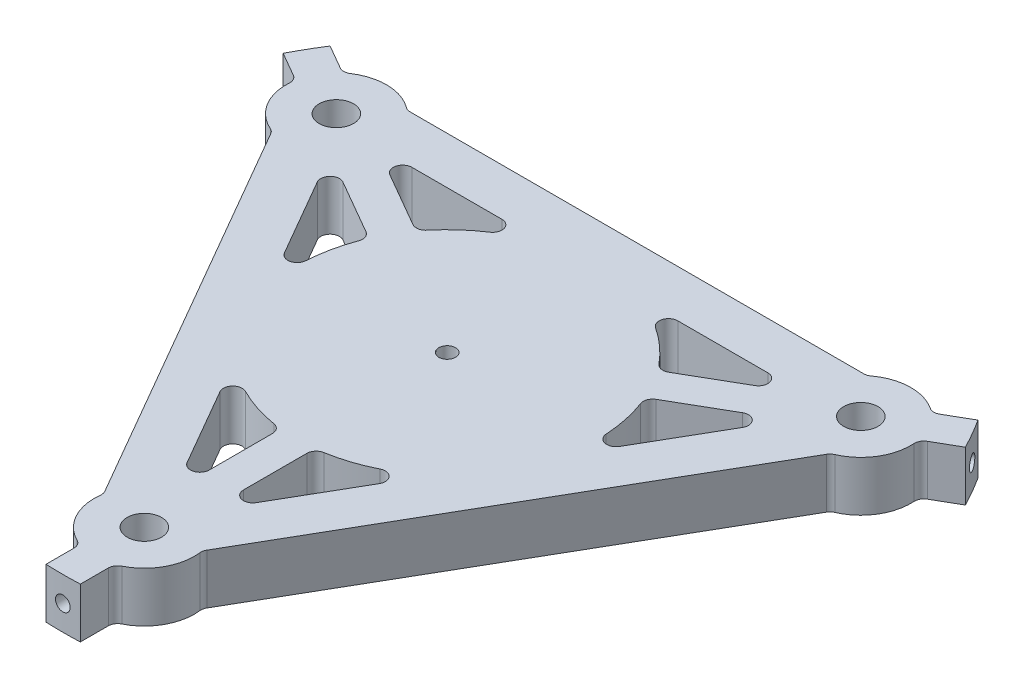
SolidWorks part; units mm, degrees
ref_plane "Front Plane" through (0, 0, 0) normal (0, 0, 1) x (1, 0, 0)
ref_plane "Top Plane" through (0, 0, 0) normal (0, 1, 0) x (1, 0, 0)
ref_plane "Right Plane" through (0, 0, 0) normal (1, 0, 0) x (0, 0, -1)
sketch "Sketch1" plane through (0, 0, 0) normal (0, 1, 0) x (1, 0, 0)
  line L0 (-3.2639, -67.6472) -> (-3.2639, -72.952)
  line L1 (3.2639, -67.6472) -> (3.2639, -72.952)
  line L2 (3.2639, -41.9471) -> (3.2639, -29.9313)
  line L3 (-3.2639, -41.9471) -> (-3.2639, -29.9313)
  line L4 (-34.6953, 23.8002) -> (-24.2893, 17.7923)
  line L5 (-37.9592, 18.1469) -> (-27.5532, 12.139)
  line L6 (-56.9522, 36.6502) -> (-61.5464, 39.3026)
  line L7 (-60.2161, 30.997) -> (-64.8103, 33.6494)
  line L8 (37.9592, 18.1469) -> (27.5532, 12.139)
  line L9 (34.6953, 23.8002) -> (24.2893, 17.7923)
  line L10 (60.2161, 30.997) -> (64.8103, 33.6494)
  line L11 (56.9522, 36.6502) -> (61.5464, 39.3026)
  line L12 (0, 0) -> (0, -57.531) construction
  line L13 (0, 0) -> (-49.8233, 28.7655) construction
  line L14 (0, 0) -> (49.8233, 28.7655) construction
  line L15 (40.388, 15.7181) -> (31.8393, 0.9115)
  line L16 (9.6892, -55.3504) -> (52.7795, 19.2841)
  line L17 (-6.5817, -42.8361) -> (-15.1303, -28.0294)
  line L18 (-52.7795, 19.2841) -> (-9.6892, -55.3504)
  line L19 (-43.0903, 36.0663) -> (43.0903, 36.0663)
  line L20 (-33.8063, 27.118) -> (-16.709, 27.118)
  line L21 (16.709, 27.118) -> (33.8063, 27.118)
  line L22 (-31.8393, 0.9115) -> (-40.388, 15.7181)
  line L23 (15.1303, -28.0294) -> (6.5817, -42.8361)
  arc A0 (-3.2639, -72.952) -> (3.2639, -72.952) centre (0, 0) ccw
  arc A1 (4.7466, -28.178) -> (12.7944, -25.5506) centre (0, 0) ccw
  arc A2 (-9.4626, -56.4426) -> (-4.2488, -66.0559) centre (0, -57.531) ccw
  circle A3 centre (0, -57.531) radius 3.2639
  arc A4 (4.2488, -66.0559) -> (9.4626, -56.4426) centre (0, -57.531) ccw
  arc A5 (-44.1494, 36.4162) -> (-55.0817, 36.7075) centre (-49.8233, 28.7655) ccw
  arc A6 (-61.5464, 39.3026) -> (-64.8103, 33.6494) centre (0, 0) ccw
  arc A7 (-59.3305, 29.3484) -> (-53.612, 20.0264) centre (-49.8233, 28.7655) ccw
  circle A8 centre (-49.8233, 28.7655) radius 3.2639
  arc A9 (53.612, 20.0264) -> (59.3305, 29.3484) centre (49.8233, 28.7655) ccw
  arc A10 (64.8103, 33.6494) -> (61.5464, 39.3026) centre (0, 0) ccw
  arc A11 (55.0817, 36.7075) -> (44.1494, 36.4162) centre (49.8233, 28.7655) ccw
  circle A12 centre (49.8233, 28.7655) radius 3.2639
  arc A13 (-26.7762, 9.9784) -> (-28.5247, 1.695) centre (0, 0) ccw
  arc A14 (22.0296, 18.1997) -> (15.7302, 23.8556) centre (0, 0) ccw
  circle A15 centre (0, 0) radius 1.5875
  arc A16 (-12.7944, -25.5506) -> (-4.7466, -28.178) centre (0, 0) ccw
  arc A17 (28.5247, 1.695) -> (26.7762, 9.9784) centre (0, 0) ccw
  arc A18 (-15.7302, 23.8556) -> (-22.0296, 18.1997) centre (0, 0) ccw
  arc A19 (37.9592, 18.1469) -> (40.388, 15.7181) centre (38.8482, 16.6071) cw
  arc A20 (26.7762, 9.9784) -> (27.5532, 12.139) centre (28.4422, 10.5992) cw
  arc A21 (3.2639, -29.9313) -> (4.7466, -28.178) centre (5.0419, -29.9313) cw
  arc A22 (15.1303, -28.0294) -> (12.7944, -25.5506) centre (13.5905, -27.1404) ccw
  arc A23 (6.5817, -42.8361) -> (3.2639, -41.9471) centre (5.0419, -41.9471) cw
  arc A24 (-6.5817, -42.8361) -> (-3.2639, -41.9471) centre (-5.0419, -41.9471) ccw
  arc A25 (-3.2639, -29.9313) -> (-4.7466, -28.178) centre (-5.0419, -29.9313) ccw
  arc A26 (-15.1303, -28.0294) -> (-12.7944, -25.5506) centre (-13.5905, -27.1404) cw
  arc A27 (-31.8393, 0.9115) -> (-28.5247, 1.695) centre (-30.2996, 1.8005) ccw
  arc A28 (-26.7762, 9.9784) -> (-27.5532, 12.139) centre (-28.4422, 10.5992) ccw
  arc A29 (-40.388, 15.7181) -> (-37.9592, 18.1469) centre (-38.8482, 16.6071) cw
  arc A30 (-24.2893, 17.7923) -> (-22.0296, 18.1997) centre (-23.4003, 19.3321) ccw
  arc A31 (-34.6953, 23.8002) -> (-33.8063, 27.118) centre (-33.8063, 25.34) cw
  arc A32 (-15.7302, 23.8556) -> (-16.709, 27.118) centre (-16.709, 25.34) ccw
  arc A33 (-4.2488, -66.0559) -> (-3.2639, -67.6472) centre (-5.0419, -67.6472) cw
  arc A34 (3.2639, -67.6472) -> (4.2488, -66.0559) centre (5.0419, -67.6472) cw
  arc A35 (9.6892, -55.3504) -> (9.4626, -56.4426) centre (11.229, -56.2394) ccw
  arc A36 (-9.4626, -56.4426) -> (-9.6892, -55.3504) centre (-11.229, -56.2394) ccw
  arc A37 (-52.7795, 19.2841) -> (-53.612, 20.0264) centre (-54.3193, 18.3951) ccw
  arc A38 (-59.3305, 29.3484) -> (-60.2161, 30.997) centre (-61.1051, 29.4572) ccw
  arc A39 (-56.9522, 36.6502) -> (-55.0817, 36.7075) centre (-56.0632, 38.19) ccw
  arc A40 (-44.1494, 36.4162) -> (-43.0903, 36.0663) centre (-43.0903, 37.8443) ccw
  arc A41 (43.0903, 36.0663) -> (44.1494, 36.4162) centre (43.0903, 37.8443) ccw
  arc A42 (52.7795, 19.2841) -> (53.612, 20.0264) centre (54.3193, 18.3951) cw
  arc A43 (55.0817, 36.7075) -> (56.9522, 36.6502) centre (56.0632, 38.19) ccw
  arc A44 (59.3305, 29.3484) -> (60.2161, 30.997) centre (61.1051, 29.4572) cw
  arc A45 (15.7302, 23.8556) -> (16.709, 27.118) centre (16.709, 25.34) cw
  arc A46 (34.6953, 23.8002) -> (33.8063, 27.118) centre (33.8063, 25.34) ccw
  arc A47 (22.0296, 18.1997) -> (24.2893, 17.7923) centre (23.4003, 19.3321) ccw
  arc A48 (31.8393, 0.9115) -> (28.5247, 1.695) centre (30.2996, 1.8005) cw
  point P53 (18.9808, -21.3603)
  point P64 (-27.9889, -5.7577)
  point P77 (-3.2639, -66.4793)
  point P80 (3.2639, -66.4793)
  point P103 (9.0082, 27.118)
  point P110 (0, 0)
  dimension "D1" = 146.05
  dimension "D2" = 57.15
  dimension "D3" = 19.05
  dimension "D4" = 6.5278
  dimension "D9" = 3.175
  dimension "D10" = 1.778
  dimension "D11" = 1.778
  dimension "D5" = 57.531
  dimension "D7" = 120
  dimension "D8" = 120
  dimension "D6" = 3
extrude "Boss-Extrude1" add sketch "Sketch1" along normal mid plane 9.525
sketch "Sketch2" plane through (0, 0, 0) normal (0, 0, 1) x (1, 0, 0)
  line L0 (0, 4.7625) -> (0, -4.7625) construction
  line L1 (3.2639, 4.7625) -> (-3.2639, 4.7625) construction
  line L2 (-3.2639, -4.7625) -> (3.2639, -4.7625) construction
ref_plane "Plane1" through (0, 0, 73.025) normal (0, 0, 1) x (1, 0, 0)
sketch "Sketch3" plane through (0, 0, 73.025) normal (0, 0, 1) x (1, 0, 0)
  circle A0 centre (0, 0) radius 1.397
  dimension "D1" = 2.794
extrude "Cut-Extrude1" cut sketch "Sketch3" against normal blind 6.35
pattern_circular "CirPattern1" count 3 over 360 about axis through (0, 0, 0) along (0, 1, 0) of "Cut-Extrude1"
sketch "Sketch4" plane through (0, -4.7625, 0) normal (0, -1, 0) x (1, 0, 0)
  circle A0 centre (-22.821, 8.6514) radius 1.5875
  point P2 (-28.75, 7.5295)
  point P3 (-27.835, 10.6137)
  point P4 (-22.6564, 10.4425)
  point P5 (-22.821, 8.6514)
  dimension "D1" = 3.175
